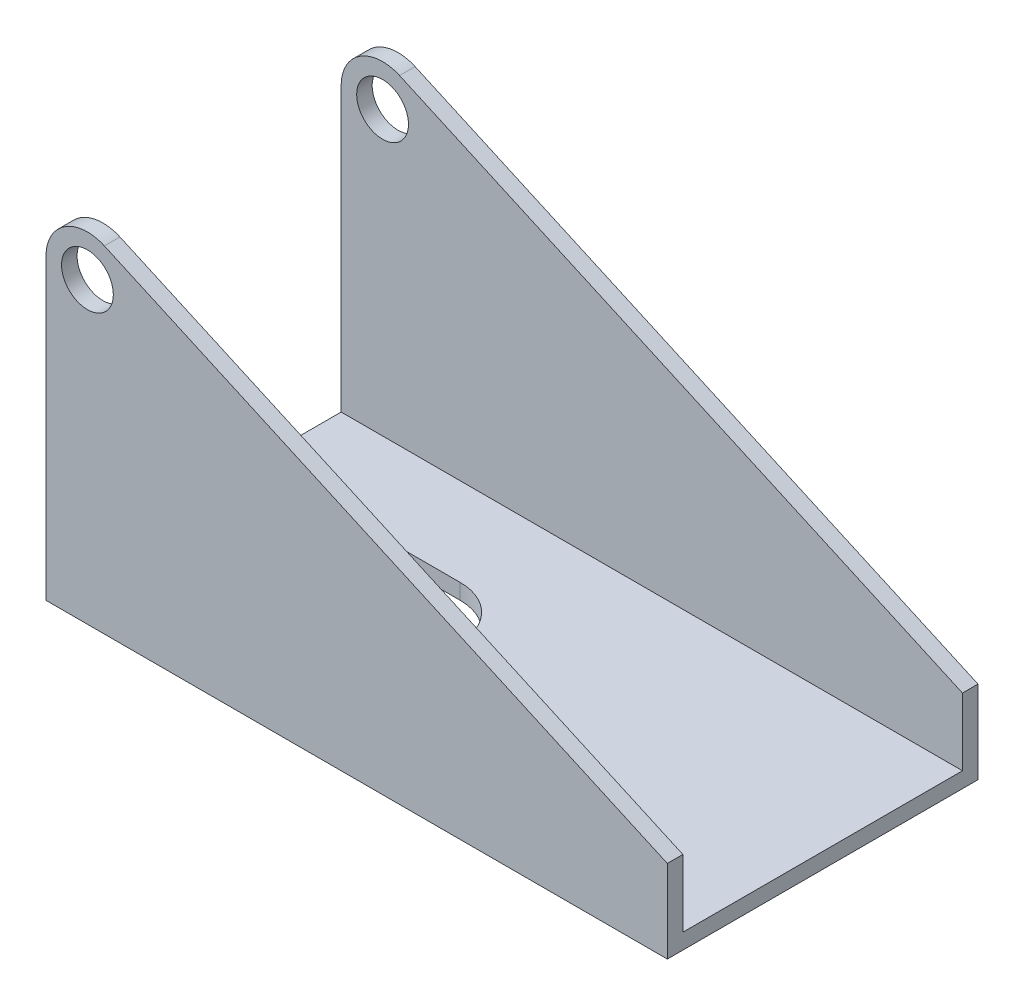
SolidWorks part; units mm, degrees
ref_plane "Alzado" through (0, 0, 0) normal (0, 0, 1) x (1, 0, 0)
ref_plane "Planta" through (0, 0, 0) normal (0, 1, 0) x (1, 0, 0)
ref_plane "Vista lateral" through (0, 0, 0) normal (1, 0, 0) x (0, 0, -1)
sketch "Croquis1" plane through (0, 0, 0) normal (0, 0, 1) x (1, 0, 0)
  line L0 (-13.9102, 10.6588) -> (-13.9102, 39.4725)
  line L1 (-8.2687, 43.1202) -> (46.0898, 18.6588)
  line L2 (46.0898, 10.6588) -> (-13.9102, 10.6588)
  line L3 (46.0898, 18.6588) -> (46.0898, 10.6588)
  arc A0 (-13.9102, 39.4725) -> (-8.2687, 43.1202) centre (-9.9102, 39.4725) cw
  point P6 (-13.9102, 45.6588)
  dimension "D3" = 4
  dimension "D1" = 60
  dimension "D2" = 35
  dimension "D4" = 8
extrude "Saliente-Extruir1" add sketch "Croquis1" along normal blind 30
sketch "Croquis2" plane through (0, 0, 30) normal (0, 0, 1) x (1, 0, 0)
  circle A0 centre (-9.9102, 39.4725) radius 2.5
  dimension "D1" = 5
extrude "Cortar-Extruir1" cut sketch "Croquis2" against normal through all
sketch "Croquis3" plane through (-13.9102, 0, 0) normal (-1, 0, 0) x (0, 0, 1)
  line L0 (30, 43.4725) -> (0, 43.4725) construction
  line L1 (1.5, 74.7861) -> (28.5, 74.7861)
  line L2 (1.5, 74.7861) -> (1.5, 12.1588)
  line L3 (1.5, 12.1588) -> (28.5, 12.1588)
  line L4 (28.5, 74.7861) -> (28.5, 12.1588)
  line L5 (1.5, 74.7861) -> (28.5, 12.1588) construction
  line L6 (1.5, 12.1588) -> (28.5, 74.7861) construction
  line L7 (0, 18.6588) -> (0, 43.1202) construction
  line L8 (30, 10.6588) -> (0, 10.6588) construction
  point P0 (15, 43.4725)
  point P7 (0, 30.8895)
  dimension "D1" = 1.5
  dimension "D2" = 1.5
extrude "Cortar-Extruir2" cut sketch "Croquis3" against normal blind 72
sketch "Croquis4" plane through (0, 12.1588, 0) normal (0, 1, 0) x (1, 0, 0)
  line L0 (-13.9102, -1.5) -> (-13.9102, -28.5) construction
  line L1 (-33.9102, -20) -> (6.0898, -20)
  line L2 (-33.9102, -20) -> (-33.9102, -10)
  line L3 (-33.9102, -10) -> (6.0898, -10)
  line L5 (-33.9102, -20) -> (-13.9102, -15) construction
  line L6 (-33.9102, -10) -> (-13.9102, -15) construction
  arc A0 (6.0898, -20) -> (6.0898, -10) centre (6.0898, -15) ccw
  point P0 (-13.9102, -15)
  dimension "D1" = 10
  dimension "D2" = 40
extrude "Cortar-Extruir3" cut sketch "Croquis4" against normal through all
